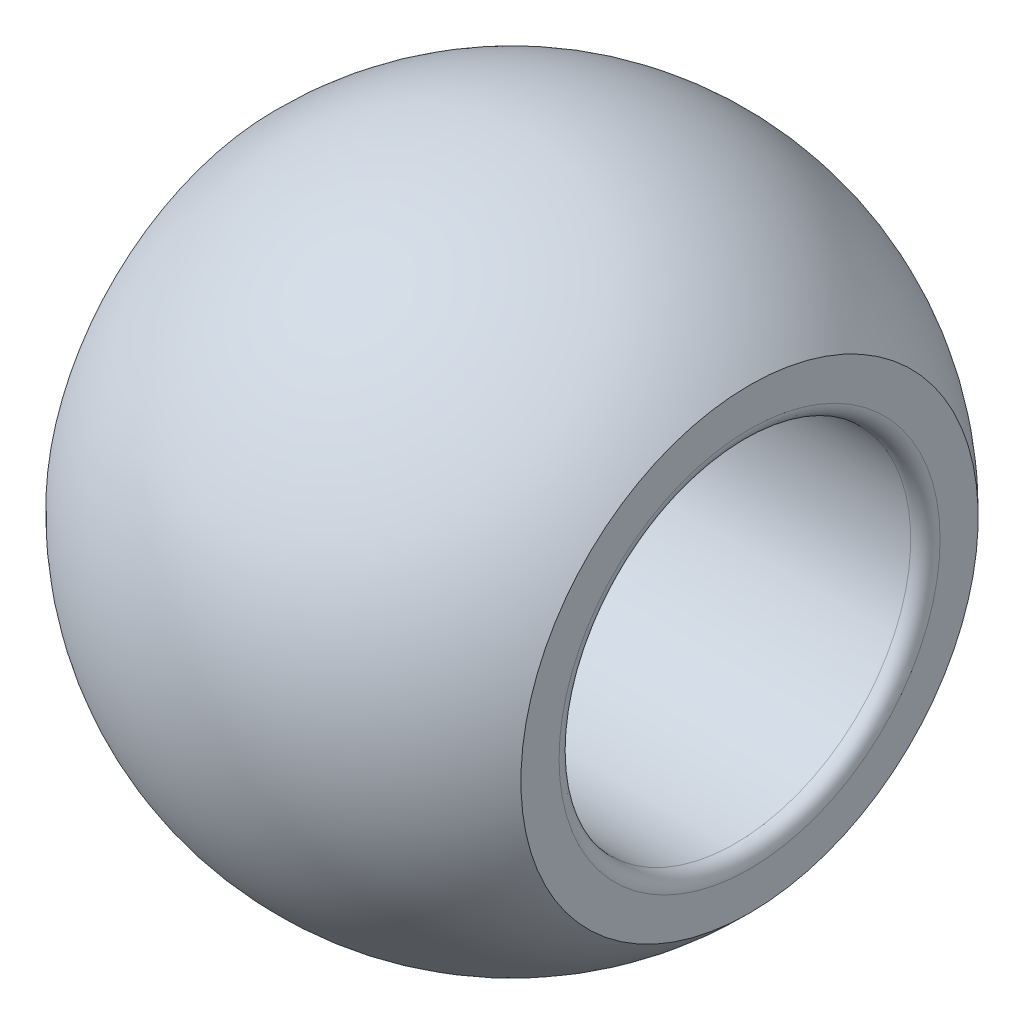
SolidWorks part; units mm, degrees
material "1023 탄소 강판(SS)"
ref_plane "정면" through (0, 0, 0) normal (0, 0, 1) x (1, 0, 0)
ref_plane "윗면" through (0, 0, 0) normal (0, 1, 0) x (1, 0, 0)
ref_plane "우측면" through (0, 0, 0) normal (1, 0, 0) x (0, 0, -1)
sketch "스케치1" plane through (0, 0, 0) normal (0, 0, 1) x (1, 0, 0)
  line L0 (-8.1055, 7.8015) -> (-8.1055, 6.5)
  line L1 (-7.6055, 6) -> (7.6055, 6)
  line L2 (8.1055, 6.5) -> (8.1055, 7.8015)
  line L3 (-8, 0) -> (8, 0) construction
  line L4 (0, 0) -> (0, 11.7945) construction
  line L5 (-13.3383, 0) -> (13.725, 0) construction
  arc A0 (-8.1055, 6.5) -> (-7.6055, 6) centre (-7.6055, 6.5) ccw
  arc A1 (7.6055, 6) -> (8.1055, 6.5) centre (7.6055, 6.5) ccw
  arc A2 (8.1055, 7.8015) -> (-8.1055, 7.8015) centre (0, 0) ccw
  dimension "D2" = 11.25
  dimension "D1" = 6
  dimension "D3" = 1.3015
  dimension "D4" = 1.3015
revolve "회전1" add sketch "스케치1" angle 360 about L3
ref_plane "평면1" through (0, 0, 0) normal (1, 0, 0) x (0, 0, -1)
